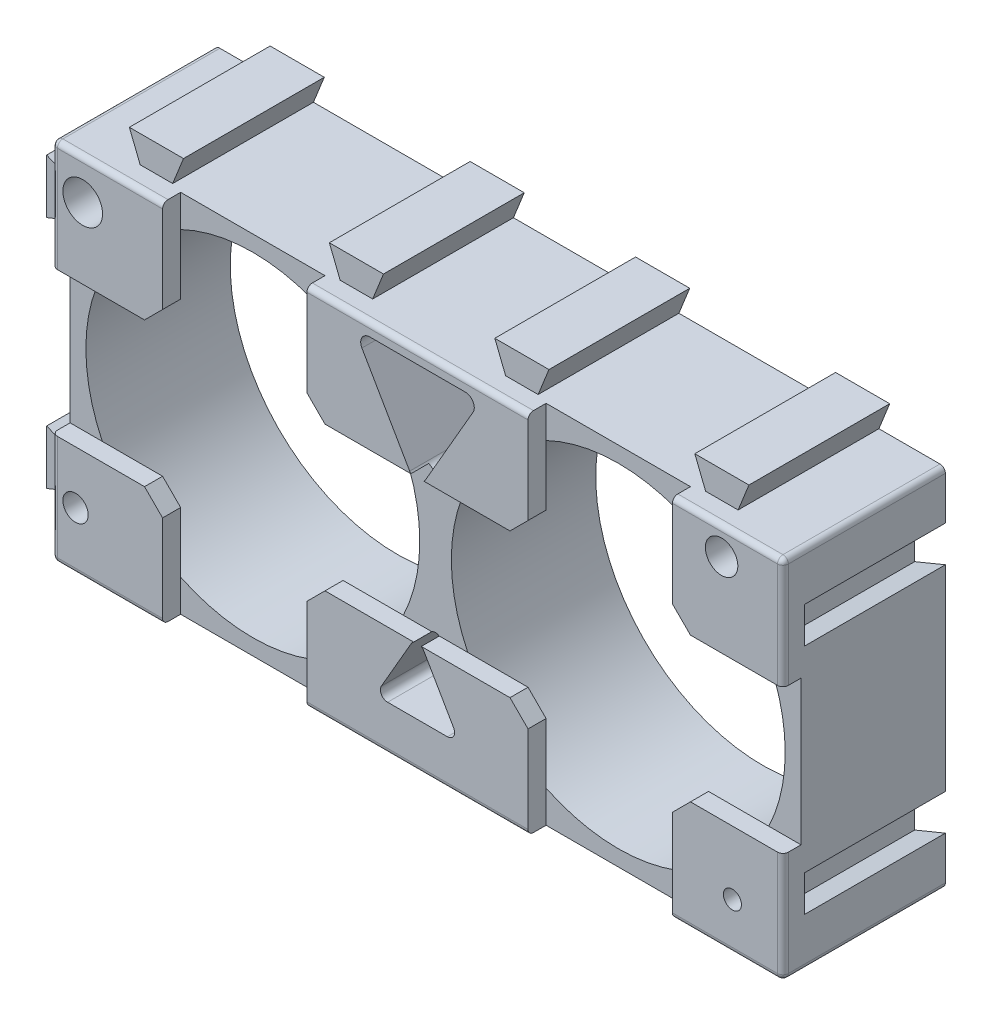
SolidWorks part; units mm, degrees
ref_plane "Front" through (0, 0, 0) normal (0, 0, 1) x (1, 0, 0)
ref_plane "Top" through (0, 0, 0) normal (0, 1, 0) x (1, 0, 0)
ref_plane "Right" through (0, 0, 0) normal (1, 0, 0) x (0, 0, -1)
sketch "Эскиз1" plane through (0, 0, 0) normal (0, 0, 1) x (1, 0, 0)
  line L1 (-20.25, 10.125) -> (20.25, 10.125)
  line L2 (-20.25, 10.125) -> (-20.25, -10.125)
  line L3 (-20.25, -10.125) -> (20.25, -10.125)
  line L4 (20.25, 10.125) -> (20.25, -10.125)
  line L5 (0, -10.125) -> (0, 10.125) construction
  line L6 (-20.25, 0) -> (20.25, 0) construction
  point P0 (0, 0)
  dimension "D1" = 20.25
  dimension "D2" = 40.5
extrude "Бобышка-Вытянуть1" add sketch "Эскиз1" along normal blind 9
sketch "Эскиз2" plane through (0, 0, 9) normal (0, 0, 1) x (1, 0, 0)
  line L0 (0, 10.125) -> (0, -10.125) construction
  line L1 (20.25, 10.125) -> (-20.25, 10.125) construction
  line L2 (-20.25, -10.125) -> (20.25, -10.125) construction
  line L3 (0, 0) -> (-20.25, 0) construction
  line L4 (-20.25, 10.125) -> (-20.25, -10.125) construction
  circle A0 centre (-10.125, 0) radius 9.25
  circle A1 centre (10.125, 0) radius 9.25
  dimension "D1" = 18.5
extrude "Вырез-Вытянуть1" cut sketch "Эскиз2" against normal blind 9 from offset 1 offset against normal yes
sketch "Эскиз3" plane through (0, 0, 9) normal (0, 0, 1) x (1, 0, 0)
  line L1 (-14.125, 12.5) -> (-6.125, 12.5)
  line L2 (-14.125, 12.5) -> (-14.125, -12.5)
  line L3 (-14.125, -12.5) -> (-6.125, -12.5)
  line L4 (-6.125, 12.5) -> (-6.125, -12.5)
  line L5 (-10.125, -12.5) -> (-10.125, 12.5) construction
  line L6 (-14.125, 0) -> (-6.125, 0) construction
  line L7 (-22.5, 4) -> (22.5, 4)
  line L8 (-22.5, 4) -> (-22.5, -4)
  line L9 (-22.5, -4) -> (22.5, -4)
  line L10 (22.5, 4) -> (22.5, -4)
  line L11 (0, -4) -> (0, 4) construction
  line L12 (-22.5, 0) -> (22.5, 0) construction
  line L13 (6.125, 12.5) -> (14.125, 12.5)
  line L14 (6.125, 12.5) -> (6.125, -12.5)
  line L15 (6.125, -12.5) -> (14.125, -12.5)
  line L16 (14.125, 12.5) -> (14.125, -12.5)
  line L17 (10.125, -12.5) -> (10.125, 12.5) construction
  line L18 (6.125, 0) -> (14.125, 0) construction
  point P0 (-10.125, 0)
  point P4 (0, 0)
  point P11 (10.125, 0)
  line M1 (20.25, -10.125) -> (20.25, 10.125)
  line M2 (20.25, 10.125) -> (-20.25, 10.125)
  line M3 (-20.25, 10.125) -> (-20.25, -10.125)
  line M4 (-20.25, -10.125) -> (20.25, -10.125)
  dimension "D1" = 25
  dimension "D2" = 8
  dimension "D3" = 8
  dimension "D4" = 45
  dimension "D5" = 25
  dimension "D6" = 8
extrude "Вырез-Вытянуть2" cut sketch "Эскиз3" against normal blind 1 contours L9 L2 L7 M3 | L2 L9 L4 L7 | L14 L7 L4 L9 | L16 L7 L14 L9 | L7 L16 L9 M1 | L16 L14 L7 M2 | L2 L7 L4 M2 | L9 L2 L4 M4 | L16 L9 L14 M4
chamfer "Фаска1" distance 1 angle 45 8 edges at (14.125, -4, 8.5) (-6.125, -4, 8.5) (-14.125, -4, 8.5) (6.125, -4, 8.5) (6.125, 4, 8.5) (14.125, 4, 8.5) (-6.125, 4, 8.5) (-14.125, 4, 8.5)
sketch "Эскиз4" plane through (0, 0, 9) normal (0, 0, 1) x (1, 0, 0)
  line L0 (0, 10.125) -> (0, -10.125) construction
  line L1 (6.125, 10.125) -> (-6.125, 10.125) construction
  line L2 (-6.125, -10.125) -> (6.125, -10.125) construction
  line L3 (0, -10.125) -> (20.25, 0) construction
  line L4 (20.25, -4) -> (20.25, 4) construction
  line L5 (20.25, 0) -> (-20.25, 0) construction
  line L6 (-20.25, 4) -> (-20.25, -4) construction
  line L8 (3.0799, 8.675) -> (0.433, 4.0905)
  line L9 (-0.433, 4.0905) -> (-3.0799, 8.675)
  line L11 (-2.6469, 9.425) -> (2.6469, 9.425)
  line L12 (-0.3464, -4.14) -> (-2.0036, -7.0103)
  line L13 (-1.6572, -7.6103) -> (1.6572, -7.6103)
  line L14 (2.0036, -7.0103) -> (0.3464, -4.14)
  line L15 (-14.125, 10.125) -> (-20.25, 10.125) construction
  line L16 (-20.25, 10.125) -> (-20.25, 4) construction
  line L17 (-20.25, -10.125) -> (-14.125, -10.125) construction
  line L18 (-20.25, -4) -> (-20.25, -10.125) construction
  line L19 (20.25, 4) -> (20.25, 10.125) construction
  line L20 (20.25, 10.125) -> (14.125, 10.125) construction
  line L21 (20.25, -10.125) -> (20.25, -4) construction
  line L22 (14.125, -10.125) -> (20.25, -10.125) construction
  arc A0 (-3.0799, 8.675) -> (-2.6469, 9.425) centre (-2.6469, 8.925) cw
  arc A1 (0.433, 4.0905) -> (-0.433, 4.0905) centre (0, 4.3405) cw
  arc A2 (2.6469, 9.425) -> (3.0799, 8.675) centre (2.6469, 8.925) cw
  arc A3 (1.6572, -7.6103) -> (2.0036, -7.0103) centre (1.6572, -7.2103) ccw
  arc A4 (-2.0036, -7.0103) -> (-1.6572, -7.6103) centre (-1.6572, -7.2103) ccw
  arc A5 (-0.3464, -4.14) -> (0.3464, -4.14) centre (0, -4.34) cw
  circle A6 centre (-18.55, 7.925) radius 1.1
  circle A7 centre (-18.95, -6.925) radius 0.7
  circle A8 centre (16.85, 8.625) radius 0.9
  circle A9 centre (17.45, -7.525) radius 0.5
  point P12 (0, 9.425)
  point P20 (0, 3.3405)
  point P30 (-2.35, -7.6103)
  point P33 (0, -3.54)
  dimension "D2" = 0.5
  dimension "D4" = 0.4
  dimension "D7" = 2.2
  dimension "D8" = 2.2
  dimension "D10" = 1.4
  dimension "D13" = 1.8
  dimension "D16" = 1
  dimension "D1" = 0.7
  dimension "D3" = 4.7
  dimension "D5" = 4.3405
  dimension "D6" = 4.34
  dimension "D9" = 1.7
  dimension "D11" = 3.2
  dimension "D12" = 1.3
  dimension "D14" = 3.4
  dimension "D15" = 1.5
  dimension "D17" = 2.8
  dimension "D18" = 2.6
extrude "Вырез-Вытянуть3" cut sketch "Эскиз4" against normal blind 7.2
sketch "Эскиз5" plane through (0, 0, 0) normal (0, 0, -1) x (-1, 0, 0)
  line L0 (0, 10.125) -> (0, -10.125) construction
  line L1 (-20.25, 10.125) -> (20.25, 10.125) construction
  line L2 (20.25, -10.125) -> (-20.25, -10.125) construction
  line L3 (-10.125, 11.625) -> (-10.125, -11.625) construction
  line L4 (-21.75, 10.125) -> (-21.75, -11.625) construction
  line L5 (-21.75, -11.625) -> (20.2749, -11.625) construction
  line L6 (-20.25, -10.125) -> (-20.25, 10.125) construction
  line L7 (-10.125, 0) -> (-21.75, 0) construction
  line L8 (-21.75, 8) -> (-21.75, 5) construction
  line L9 (-21.75, 6.5) -> (-20.25, 6.5) construction
  line L10 (-20.25, 6.5) -> (-20.25, 7.4) construction
  line L11 (-20.25, 7.4) -> (-21.75, 8) construction
  line L12 (-20.25, 7.4) -> (-20.25, 5.6) construction
  line L13 (-20.25, 5.6) -> (-21.75, 5) construction
  line L14 (-20.25, 7.4) -> (-21.75, 8) construction
  line L19 (-20.25, -7.4) -> (-20.25, -5.6) construction
  line L20 (-20.25, -5.6) -> (-21.75, -5) construction
  line L21 (-21.75, -8) -> (-21.75, -5) construction
  line L22 (-20.25, -7.4) -> (-21.75, -8) construction
  line L23 (-14.1659, -11.625) -> (-17.1659, -11.625) construction
  line L24 (-15.6659, -11.625) -> (-15.6659, -10.125) construction
  line L25 (-15.6659, -10.125) -> (-16.5659, -10.125) construction
  line L26 (-16.5659, -10.125) -> (-14.7659, -10.125) construction
  line L27 (-16.5659, -10.125) -> (-17.1659, -11.625) construction
  line L28 (-14.1659, -11.625) -> (-14.7659, -10.125) construction
  line L29 (-6.0841, -11.625) -> (-3.0841, -11.625) construction
  line L30 (-3.6841, -10.125) -> (-3.0841, -11.625) construction
  line L31 (-3.6841, -10.125) -> (-5.4841, -10.125) construction
  line L32 (-6.0841, -11.625) -> (-5.4841, -10.125) construction
  line L33 (14.1659, -11.625) -> (17.1659, -11.625) construction
  line L34 (16.5659, -10.125) -> (17.1659, -11.625) construction
  line L35 (16.5659, -10.125) -> (14.7659, -10.125) construction
  line L36 (14.1659, -11.625) -> (14.7659, -10.125) construction
  line L37 (6.0841, -11.625) -> (5.4841, -10.125) construction
  line L38 (3.6841, -10.125) -> (5.4841, -10.125) construction
  line L39 (3.6841, -10.125) -> (3.0841, -11.625) construction
  line L40 (6.0841, -11.625) -> (3.0841, -11.625) construction
  line L41 (-14.1659, 11.625) -> (-17.1659, 11.625)
  line L42 (-16.5659, 10.125) -> (-17.1659, 11.625)
  line L43 (-16.5659, 10.125) -> (-14.7659, 10.125)
  line L44 (-14.1659, 11.625) -> (-14.7659, 10.125)
  line L45 (-6.0841, 11.625) -> (-5.4841, 10.125)
  line L46 (-3.6841, 10.125) -> (-5.4841, 10.125)
  line L47 (-3.6841, 10.125) -> (-3.0841, 11.625)
  line L48 (-6.0841, 11.625) -> (-3.0841, 11.625)
  line L49 (6.0841, 11.625) -> (3.0841, 11.625)
  line L50 (3.6841, 10.125) -> (3.0841, 11.625)
  line L51 (3.6841, 10.125) -> (5.4841, 10.125)
  line L52 (6.0841, 11.625) -> (5.4841, 10.125)
  line L53 (14.1659, 11.625) -> (14.7659, 10.125)
  line L54 (16.5659, 10.125) -> (14.7659, 10.125)
  line L55 (16.5659, 10.125) -> (17.1659, 11.625)
  line L56 (14.1659, 11.625) -> (17.1659, 11.625)
  line L57 (20.25, 7.4) -> (20.25, 5.6)
  line L58 (20.25, 5.6) -> (21.75, 5)
  line L59 (21.75, 8) -> (21.75, 5)
  line L60 (20.25, 7.4) -> (21.75, 8)
  line L61 (20.25, -7.4) -> (21.75, -8)
  line L62 (21.75, -8) -> (21.75, -5)
  line L63 (20.25, -5.6) -> (21.75, -5)
  line L64 (20.25, -7.4) -> (20.25, -5.6)
  dimension "D1" = 1.5
  dimension "D2" = 1.5
  dimension "D3" = 3
  dimension "D4" = 6.5
  dimension "D5" = 1.8
  dimension "D6" = 5.5409
  dimension "D7" = 3
  dimension "D8" = 1.8
extrude "Бобышка-Вытянуть2" add sketch "Эскиз5" against normal blind 7.8
sketch "Эскиз6" plane through (0, 0, 0) normal (0, 0, -1) x (-1, 0, 0)
  line L0 (-15.6659, -11.625) -> (-15.6659, 10.125) construction
  line L2 (-20.25, 10.125) -> (-16.5659, 10.125) construction
  line L3 (-20.25, 8.425) -> (18.55, 8.425) construction
  line L5 (-4.5841, -11.625) -> (-4.5841, 10.125) construction
  line L6 (-20.25, -10.125) -> (-20.25, 10.125) construction
  line L8 (4.5841, -11.625) -> (4.5841, 10.125) construction
  line L9 (18.55, 8.425) -> (18.55, -10.125) construction
  line L11 (15.6659, -11.625) -> (15.6659, 10.125) construction
  line L12 (20.25, -10.125) -> (-20.25, -10.125) construction
  line L14 (-21.75, 6.5) -> (20.25, 6.5) construction
  line L15 (20.25, 10.125) -> (20.25, 7.4) construction
  line L16 (-17.3659, 8.425) -> (-16.6659, 10.125) construction
  line L18 (-21.75, -6.5) -> (20.25, -6.5) construction
  line L19 (-13.9659, 8.425) -> (-17.3659, 8.425) construction
  line L20 (-16.6659, 10.125) -> (-14.6659, 10.125) construction
  line L21 (-14.6659, 10.125) -> (-13.9659, 8.425) construction
  line L22 (-10.125, 0) -> (-10.125, 12.9282) construction
  line L23 (0, 0) -> (0, 13.7072) construction
  line L24 (-3.5841, 10.125) -> (-5.5841, 10.125) construction
  line L25 (-2.8841, 8.425) -> (-3.5841, 10.125) construction
  line L26 (-6.2841, 8.425) -> (-2.8841, 8.425) construction
  line L27 (-5.5841, 10.125) -> (-6.2841, 8.425) construction
  line L28 (16.6659, 10.125) -> (14.6659, 10.125) construction
  line L29 (17.3659, 8.425) -> (16.6659, 10.125) construction
  line L30 (13.9659, 8.425) -> (17.3659, 8.425) construction
  line L31 (14.6659, 10.125) -> (13.9659, 8.425) construction
  line L32 (2.8841, 8.425) -> (3.5841, 10.125) construction
  line L33 (6.2841, 8.425) -> (2.8841, 8.425) construction
  line L34 (5.5841, 10.125) -> (6.2841, 8.425) construction
  line L35 (3.5841, 10.125) -> (5.5841, 10.125) construction
  line L36 (23.2815, 0) -> (0, 0) construction
  line L37 (20.25, 7.4391) -> (20.25, 5.4391) construction
  line L38 (20.25, 5.4391) -> (18.55, 4.7391) construction
  line L39 (18.55, 4.7391) -> (18.55, 8.1391) construction
  line L40 (18.55, 8.1391) -> (20.25, 7.4391) construction
  line L41 (18.55, -8.1391) -> (20.25, -7.4391) construction
  line L42 (20.25, -5.4391) -> (18.55, -4.7391) construction
  line L43 (20.25, -7.4391) -> (20.25, -5.4391) construction
  line L44 (18.55, -4.7391) -> (18.55, -8.1391) construction
  line L45 (17.3659, -8.425) -> (16.6659, -10.125)
  line L46 (13.9659, -8.425) -> (17.3659, -8.425)
  line L47 (14.6659, -10.125) -> (13.9659, -8.425)
  line L48 (16.6659, -10.125) -> (14.6659, -10.125)
  line L49 (6.2841, -8.425) -> (2.8841, -8.425)
  line L50 (5.5841, -10.125) -> (6.2841, -8.425)
  line L51 (3.5841, -10.125) -> (5.5841, -10.125)
  line L52 (2.8841, -8.425) -> (3.5841, -10.125)
  line L53 (-16.6659, -10.125) -> (-14.6659, -10.125)
  line L54 (-17.3659, -8.425) -> (-16.6659, -10.125)
  line L55 (-13.9659, -8.425) -> (-17.3659, -8.425)
  line L56 (-14.6659, -10.125) -> (-13.9659, -8.425)
  line L57 (-2.8841, -8.425) -> (-3.5841, -10.125)
  line L58 (-6.2841, -8.425) -> (-2.8841, -8.425)
  line L59 (-5.5841, -10.125) -> (-6.2841, -8.425)
  line L60 (-3.5841, -10.125) -> (-5.5841, -10.125)
  line L61 (-18.55, -4.7391) -> (-18.55, -8.1391)
  line L62 (-20.25, -5.4391) -> (-18.55, -4.7391)
  line L63 (-20.25, -7.4391) -> (-20.25, -5.4391)
  line L64 (-18.55, -8.1391) -> (-20.25, -7.4391)
  line L65 (-18.55, 8.1391) -> (-20.25, 7.4391)
  line L66 (-18.55, 4.7391) -> (-18.55, 8.1391)
  line L67 (-20.25, 5.4391) -> (-18.55, 4.7391)
  line L68 (-20.25, 7.4391) -> (-20.25, 5.4391)
  point P32 (-15.6659, 8.425)
  dimension "D1" = 1.7
  dimension "D2" = 1.7
  dimension "D3" = 3.4
  dimension "D4" = 2
  dimension "D5" = 3.4
  dimension "D6" = 2
extrude "Вырез-Вытянуть4" cut sketch "Эскиз6" against normal blind 7.8
fillet "Скругление1" radius 0.3 14 edges at (20.25, -7.0625, 9) (17.1875, 10.125, 9) (20.25, 7.0625, 9) (0, 10.125, 9) (0, -10.125, 9) (17.1875, -10.125, 9) (-17.1875, 10.125, 9) (-20.25, 7.0625, 9) (-20.25, -7.0625, 9) (-17.1875, -10.125, 9) (-20.25, -10.125, 4.5) (-20.25, 10.125, 4.5) (20.25, 10.125, 4.5) (20.25, -10.125, 4.5)
